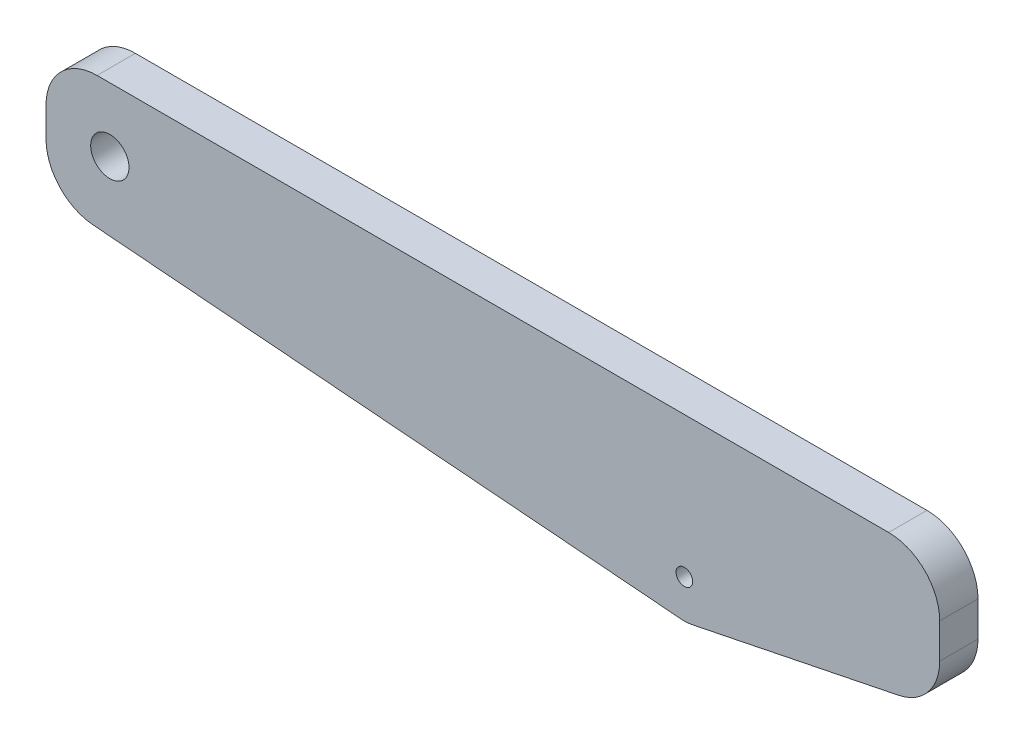
SolidWorks part; units mm, degrees
material "Beech"
ref_plane "Front Plane" through (0, 0, 0) normal (0, 0, 1) x (1, 0, 0)
ref_plane "Top Plane" through (0, 0, 0) normal (0, 1, 0) x (1, 0, 0)
ref_plane "Right Plane" through (0, 0, 0) normal (1, 0, 0) x (0, 0, -1)
sketch "Sketch1" plane through (0, 0, 0) normal (0, 0, 1) x (1, 0, 0)
  line L0 (75, 50) -> (105, 50)
  line L2 (0, 0) -> (0, 50)
  line L3 (0, 50) -> (75, 50)
  line L4 (350, 0) -> (350, 50)
  line L5 (105, 50) -> (350, 50)
  line L6 (0, 0) -> (248.7967, -20.0226)
  line L8 (350, 0) -> (252.9953, -19.7688)
  circle A0 centre (25, 25) radius 7.5
  arc A4 (248.7967, -20.0226) -> (252.9953, -19.7688) centre (250, -5.0709) ccw
  circle A5 centre (250, -5.0709) radius 3.25
  dimension "D8" = 15
  dimension "D9" = 30
  dimension "D10" = 6.5
  dimension "D1" = 350
  dimension "D2" = 50
  dimension "D3" = 25
  dimension "D4" = 25
  dimension "D11" = 250
extrude "Boss-Extrude1" add sketch "Sketch1" along normal blind 15
fillet "Fillet1" radius 20 1 edges at (0, 50, 7.5)
fillet "Fillet2" radius 20 1 edges at (0, 0, 7.5)
fillet "Fillet3" radius 20 1 edges at (350, 50, 7.5)
fillet "Fillet4" radius 20 1 edges at (350, 0, 7.5)
